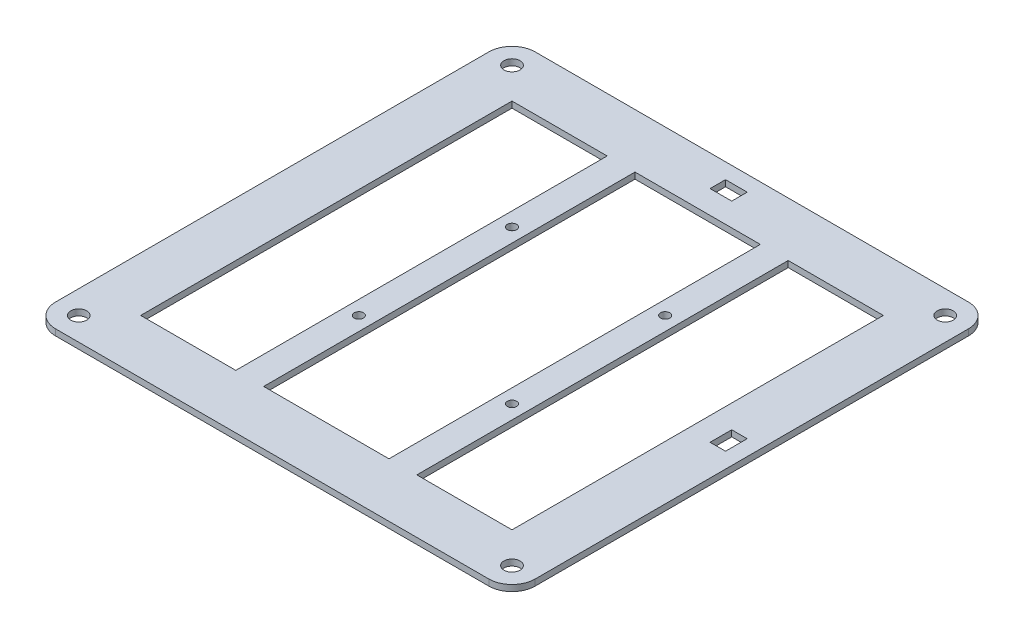
SolidWorks part; units mm, degrees
ref_plane "Alzado" through (0, 0, 0) normal (0, 0, 1) x (1, 0, 0)
ref_plane "Planta" through (0, 0, 0) normal (0, 1, 0) x (1, 0, 0)
ref_plane "Vista lateral" through (0, 0, 0) normal (1, 0, 0) x (0, 0, -1)
sketch "Croquis1" plane through (0, 0, 0) normal (0, 1, 0) x (1, 0, 0)
  line L0 (-10, -10) -> (-10, 150)
  line L1 (0, 0) -> (140, 0) construction
  line L2 (0, 0) -> (0, 140) construction
  line L3 (0, 140) -> (140, 140) construction
  line L4 (140, 0) -> (140, 140) construction
  line L5 (-10, 150) -> (150, 150)
  line L6 (150, -10) -> (150, 150)
  line L7 (-10, -10) -> (150, -10)
  line L8 (10, 10) -> (10, 130)
  line L9 (10, 130) -> (40.75, 130)
  line L10 (130, 10) -> (130, 130)
  line L11 (10, 10) -> (40.75, 10)
  line L12 (10, 70) -> (130, 70) construction
  line L13 (45.25, 70) -> (45.25, 94.75) construction
  line L14 (45.25, 70) -> (45.25, 45.25) construction
  line L15 (70, 70) -> (70, 160) construction
  line L16 (40.75, 147.7957) -> (49.75, 147.7957) construction
  line L18 (40.75, 130) -> (40.75, 10)
  line L20 (49.75, 130) -> (49.75, 10)
  line L21 (45.25, 147.7957) -> (45.25, 94.75) construction
  line L22 (49.75, 130) -> (90.25, 130)
  line L23 (49.75, 10) -> (90.25, 10)
  line L24 (10, 130) -> (130, 130) construction
  line L25 (90.25, 130) -> (90.25, 10)
  line L26 (10, 10) -> (130, 10) construction
  line L27 (99.25, 130) -> (99.25, 10)
  line L28 (99.25, 130) -> (130, 130)
  line L29 (99.25, 10) -> (130, 10)
  line L31 (137.5, 66.5) -> (142.5, 66.5)
  line L32 (137.5, 66.5) -> (137.5, 73.5)
  line L33 (137.5, 73.5) -> (142.5, 73.5)
  line L34 (142.5, 66.5) -> (142.5, 73.5)
  line L35 (137.5, 66.5) -> (142.5, 73.5) construction
  line L36 (137.5, 73.5) -> (142.5, 66.5) construction
  line L37 (66.5, 142.5) -> (73.5, 142.5)
  line L38 (66.5, 142.5) -> (66.5, 137.5)
  line L39 (66.5, 137.5) -> (73.5, 137.5)
  line L40 (73.5, 142.5) -> (73.5, 137.5)
  line L41 (66.5, 142.5) -> (73.5, 137.5) construction
  line L42 (66.5, 137.5) -> (73.5, 142.5) construction
  circle A0 centre (45.25, 94.75) radius 1.5
  circle A1 centre (45.25, 45.25) radius 1.5
  circle A2 centre (0, 140) radius 2.6
  circle A3 centre (0, 0) radius 2.6
  circle A4 centre (94.75, 94.75) radius 1.5
  circle A5 centre (94.75, 45.25) radius 1.5
  circle A6 centre (140, 0) radius 2.6
  circle A7 centre (140, 140) radius 2.6
  point P41 (140, 70)
  point P46 (70, 140)
  dimension "D4" = 3
  dimension "D8" = 5.2
  dimension "D1" = 140
  dimension "D2" = 10
  dimension "D5" = 24.75
  dimension "D6" = 24.75
  dimension "D7" = 9
  dimension "D9" = 5
  dimension "D10" = 7
  dimension "D3" = 10
extrude "Saliente-Extruir1" add sketch "Croquis1" along normal blind 2
sketch "Croquis2" plane through (0, 2, 0) normal (0, 1, 0) x (1, 0, 0)
  line L0 (0, -7.5) -> (140, -7.5)
  line L1 (147.5, 0) -> (147.5, 140)
  line L2 (140, 147.5) -> (0, 147.5)
  line L3 (-7.5, 140) -> (-7.5, 0)
  line L4 (-10, -10) -> (150, -10)
  line L5 (150, -10) -> (150, 150)
  line L6 (150, 150) -> (-10, 150)
  line L7 (-10, 150) -> (-10, -10)
  line L8 (-10, -10) -> (150, -10)
  line L9 (150, -10) -> (150, 150)
  line L10 (150, 150) -> (-10, 150)
  line L11 (-10, 150) -> (-10, -10)
  line L13 (147.5, 147.5) -> (-7.5, 147.5) construction
  line L14 (-7.5, 147.5) -> (-7.5, -7.5) construction
  line L15 (147.5, -7.5) -> (147.5, 147.5) construction
  line L16 (-7.5, -7.5) -> (147.5, -7.5) construction
  arc A0 (-7.5, 0) -> (0, -7.5) centre (0, 0) ccw
  arc A1 (140, -7.5) -> (147.5, 0) centre (140, 0) ccw
  arc A2 (147.5, 140) -> (140, 147.5) centre (140, 140) ccw
  arc A3 (0, 147.5) -> (-7.5, 140) centre (0, 140) ccw
  dimension "D3" = 15
  dimension "D1" = 0
extrude "Cortar-Extruir1" cut sketch "Croquis2" against normal blind 74
